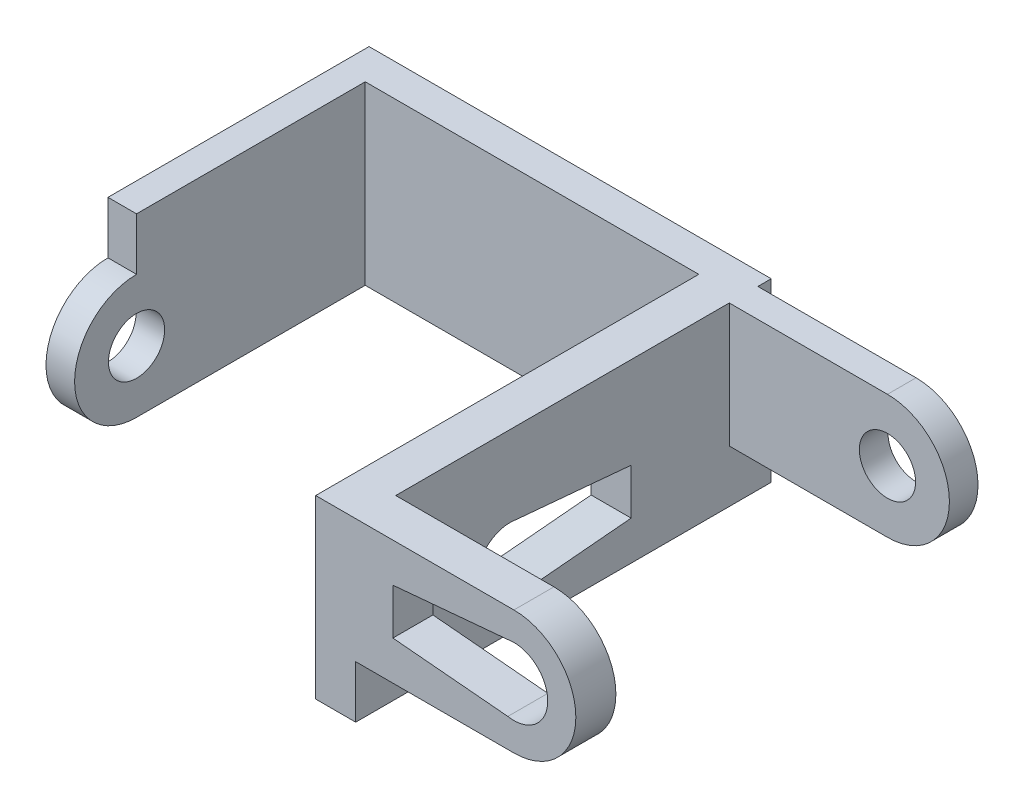
SolidWorks part; units mm, degrees
material "ABS"
ref_plane "Front Plane" through (0, 0, 0) normal (0, 0, 1) x (1, 0, 0)
ref_plane "Top Plane" through (0, 0, 0) normal (0, 1, 0) x (1, 0, 0)
ref_plane "Right Plane" through (0, 0, 0) normal (1, 0, 0) x (0, 0, -1)
sketch "Sketch1" plane through (0, 0, 0) normal (1, 0, 0) x (0, 0, -1)
  line L1 (-16.2, -30.5) -> (27.4, -30.5)
  line L2 (-16.2, -30.5) -> (-16.2, -12)
  line L3 (-16.2, -12) -> (27.4, -12)
  line L4 (27.4, -30.5) -> (27.4, -12)
extrude "Boss-Extrude1" add sketch "Sketch1" along normal mid plane 4.2 from offset 34.9
sketch "Sketch2" plane through (0, 0, 0) normal (1, 0, 0) x (0, 0, -1)
  circle A0 centre (0, -24) radius 3.55
extrude "Cut-Extrude1" cut sketch "Sketch2" against normal mid plane 4.2 from offset 34.9
sketch "Sketch3" plane through (0, 0, 0) normal (1, 0, 0) x (0, 0, -1)
  line L0 (0, -20.45) -> (12.7, -21.5967)
  line L1 (12.7, -21.5967) -> (12.7, -26.4033)
  line L2 (12.7, -26.4033) -> (0, -27.55)
  line L3 (0, -27.55) -> (0, -20.45)
  circle A0 centre (0, -24) radius 3.55 construction
extrude "Cut-Extrude2" cut sketch "Sketch3" against normal mid plane 4.2 from offset 34.9
sketch "Sketch4" plane through (0, 0, 0) normal (0, 0, 1) x (1, 0, 0)
  circle A0 centre (-16.2, -18.5) radius 6.5
extrude "Boss-Extrude2" add sketch "Sketch4" along normal mid plane 4.2 from offset 14.1
sketch "Sketch5" plane through (0, 0, 0) normal (0, 0, 1) x (1, 0, 0)
  line L0 (-37, -12) -> (-37, -30.5) construction
  line L1 (-37, -25) -> (-16.2, -25)
  line L2 (-37, -25) -> (-37, -12)
  line L3 (-37, -12) -> (-16.2, -12)
  line L4 (-16.2, -25) -> (-16.2, -12)
  circle A0 centre (-16.2, -18.5) radius 6.5 construction
extrude "Boss-Extrude3" add sketch "Sketch5" along normal mid plane 4.2 from offset 14.1
sketch "Sketch6" plane through (0, 0, 0) normal (0, 0, 1) x (1, 0, 0)
  circle A0 centre (-16.2, -18.5) radius 3.55
extrude "Cut-Extrude3" cut sketch "Sketch6" against normal mid plane 4.2 from offset 14.1
sketch "Sketch7" plane through (0, 0, 0) normal (0, 0, 1) x (1, 0, 0)
  line L0 (-16.2, -22.05) -> (-28.9, -20.9033)
  line L1 (-28.9, -20.9033) -> (-28.9, -16.0967)
  line L2 (-28.9, -16.0967) -> (-16.2, -14.95)
  line L3 (-16.2, -14.95) -> (-16.2, -22.05)
  circle A0 centre (-16.2, -18.5) radius 3.55 construction
extrude "Cut-Extrude4" cut sketch "Sketch7" against normal mid plane 4.2 from offset 14.1
sketch "Sketch8" plane through (0, 0, 0) normal (0, 0, 1) x (1, 0, 0)
  circle A0 centre (-16.2, -18.5) radius 6.5
extrude "Boss-Extrude4" add sketch "Sketch8" along normal mid plane 3 from offset 24.5
sketch "Sketch9" plane through (0, 0, 0) normal (0, 0, 1) x (1, 0, 0)
  line L0 (-37, -12) -> (-37, -30.5) construction
  line L1 (-37, -25) -> (-16.2, -25)
  line L2 (-37, -25) -> (-37, -12)
  line L3 (-37, -12) -> (-16.2, -12)
  line L4 (-16.2, -25) -> (-16.2, -12)
extrude "Boss-Extrude5" add sketch "Sketch9" along normal mid plane 3 from offset 24.5
sketch "Sketch10" plane through (0, 0, 0) normal (0, 0, 1) x (1, 0, 0)
  circle A0 centre (-16.2, -18.5) radius 2.95
extrude "Cut-Extrude5" cut sketch "Sketch10" against normal mid plane 3 from offset 24.5
sketch "Sketch11" plane through (0, 0, 0) normal (0, 0, 1) x (1, 0, 0)
  line L1 (-75, -30.5) -> (-32.8, -30.5)
  line L2 (-75, -30.5) -> (-75, -12)
  line L3 (-75, -12) -> (-32.8, -12)
  line L4 (-32.8, -30.5) -> (-32.8, -12)
extrude "Boss-Extrude6" add sketch "Sketch11" along normal mid plane 3.4 from offset 25.7
sketch "Sketch12" plane through (0, 0, 0) normal (1, 0, 0) x (0, 0, -1)
  circle A0 centre (0, -24) radius 6.5
extrude "Boss-Extrude7" add sketch "Sketch12" along normal mid plane 3 from offset 73.5
sketch "Sketch13" plane through (0, 0, 0) normal (1, 0, 0) x (0, 0, -1)
  line L0 (-16.2, -30.5) -> (27.4, -30.5) construction
  line L1 (0, -30.5) -> (27.4, -30.5)
  line L2 (0, -30.5) -> (0, -12)
  line L3 (0, -12) -> (27.4, -12)
  line L4 (27.4, -30.5) -> (27.4, -12)
extrude "Boss-Extrude8" add sketch "Sketch13" along normal mid plane 3 from offset 73.5
sketch "Sketch14" plane through (0, 0, 0) normal (1, 0, 0) x (0, 0, -1)
  circle A0 centre (0, -24) radius 2.95
extrude "Cut-Extrude6" cut sketch "Sketch14" against normal mid plane 3 from offset 73.5
